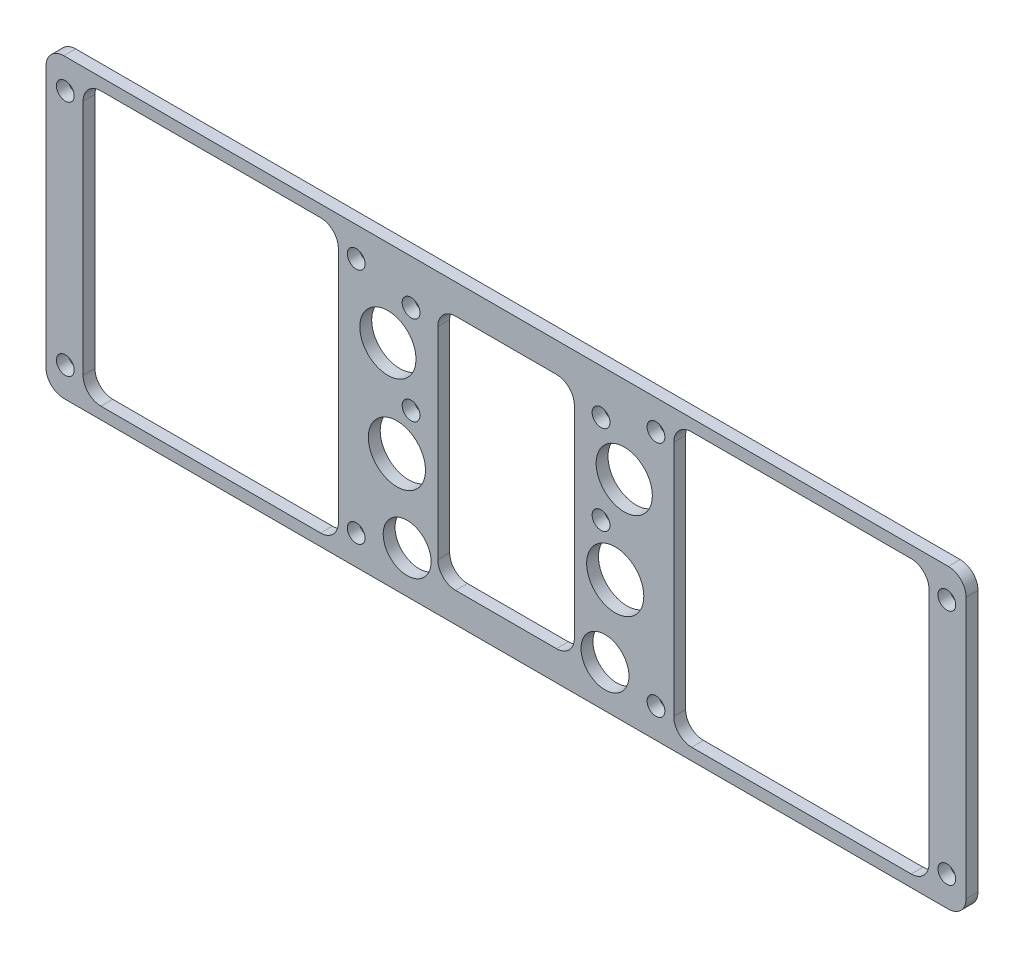
SolidWorks part; units mm, degrees
material "水绿环氧树脂"
ref_plane "前视基准面" through (0, 0, 0) normal (0, 0, 1) x (1, 0, 0)
ref_plane "上视基准面" through (0, 0, 0) normal (0, 1, 0) x (1, 0, 0)
ref_plane "右视基准面" through (0, 0, 0) normal (1, 0, 0) x (0, 0, -1)
sketch "草图1" plane through (0, 0, 0) normal (0, 0, 1) x (1, 0, 0)
  line L1 (-77.5, -25) -> (77.5, -25)
  line L2 (-77.5, -25) -> (-77.5, 25)
  line L3 (-77.5, 25) -> (77.5, 25)
  line L4 (77.5, -25) -> (77.5, 25)
  line L5 (-77.5, -25) -> (77.5, 25) construction
  line L6 (-77.5, 25) -> (77.5, -25) construction
  point P0 (0, 0)
  dimension "D1" = 50
  dimension "D2" = 155
extrude "凸台-拉伸1" add sketch "草图1" along normal blind 2
sketch "草图2" plane through (0, 0, 0) normal (0, 0, -1) x (-1, 0, 0)
  circle A8 centre (-25.25, -20) radius 1.5
  circle A9 centre (-74.25, -20) radius 1.5
  circle A10 centre (-25.25, 20) radius 1.5
  circle A11 centre (-74.25, 20) radius 1.5
  circle A12 centre (25.25, -20) radius 1.5
  circle A13 centre (74.25, -20) radius 1.5
  circle A14 centre (25.25, 20) radius 1.5
  circle A15 centre (74.25, 20) radius 1.5
  circle A20 centre (16, 2.5) radius 1.5
  circle A21 centre (16, 17.5) radius 1.5
  circle A22 centre (-16, 2.5) radius 1.5
  circle A23 centre (-16, 17.5) radius 1.5
extrude "切除-拉伸1" cut sketch "草图2" against normal blind 10
fillet "圆角1" radius 3 4 edges at (-77.5, 25, 1) (-77.5, -25, 1) (77.5, -25, 1) (77.5, 25, 1)
sketch "草图3" plane through (0, 0, 2) normal (0, 0, 1) x (1, 0, 0)
  line L0 (25.25, -20) -> (74.25, -20) construction
  line L1 (49.75, -20) -> (49.75, 0) construction
  line L2 (0, 25) -> (0, -29.9649) construction
  line L3 (74.5, 25) -> (-74.5, 25) construction
  line L4 (-28.25, -23) -> (-71.25, 23) construction
  line L5 (28.25, 23) -> (71.25, 23)
  line L6 (28.25, 23) -> (28.25, -23)
  line L7 (28.25, -23) -> (71.25, -23)
  line L8 (71.25, 23) -> (71.25, -23)
  line L9 (28.25, 23) -> (71.25, -23) construction
  line L10 (28.25, -23) -> (71.25, 23) construction
  line L11 (-28.25, 23) -> (-71.25, -23) construction
  line L12 (-49.75, -20) -> (-49.75, 0) construction
  line L13 (-25.25, -20) -> (-74.25, -20) construction
  line L14 (-71.25, 23) -> (-71.25, -23)
  line L15 (-28.25, -23) -> (-71.25, -23)
  line L16 (-28.25, 23) -> (-28.25, -23)
  line L17 (-28.25, 23) -> (-71.25, 23)
  dimension "D1" = 20
  dimension "D2" = 46
  dimension "D3" = 43
extrude "切除-拉伸2" cut sketch "草图3" against normal blind 10
fillet "圆角2" radius 3 8 edges at (-71.25, -23, 1) (-71.25, 23, 1) (71.25, -23, 1) (28.25, -23, 1) (28.25, 23, 1) (71.25, 23, 1) (-28.25, -23, 1) (-28.25, 23, 1)
sketch "草图4" plane through (0, 0, 2) normal (0, 0, 1) x (1, 0, 0)
  line L1 (-11.5, -20) -> (11.5, -20)
  line L2 (-11.5, -20) -> (-11.5, 20)
  line L3 (-11.5, 20) -> (11.5, 20)
  line L4 (11.5, -20) -> (11.5, 20)
  line L5 (-11.5, -20) -> (11.5, 20) construction
  line L6 (-11.5, 20) -> (11.5, -20) construction
  point P0 (0, 0)
  dimension "D1" = 40
  dimension "D2" = 23
extrude "切除-拉伸3" cut sketch "草图4" against normal blind 10
fillet "圆角3" radius 3 4 edges at (-11.5, -20, 1) (-11.5, 20, 1) (11.5, -20, 1) (11.5, 20, 1)
sketch "草图5" plane through (0, 0, 2) normal (0, 0, 1) x (1, 0, 0)
  line L0 (0, 25) -> (0, -29.4588) construction
  line L1 (74.5, 25) -> (-74.5, 25) construction
  circle A0 centre (19.9072, 10.3879) radius 4.7324
  circle A1 centre (18.3869, -5.0184) radius 4.8153
  circle A2 centre (16.6638, -17.8908) radius 4.0353
  circle A3 centre (-16.6638, -17.8908) radius 4.0353
  circle A4 centre (-18.3869, -5.0184) radius 4.8153
  circle A5 centre (-19.9072, 10.3879) radius 4.7324
extrude "切除-拉伸4" cut sketch "草图5" against normal blind 10
